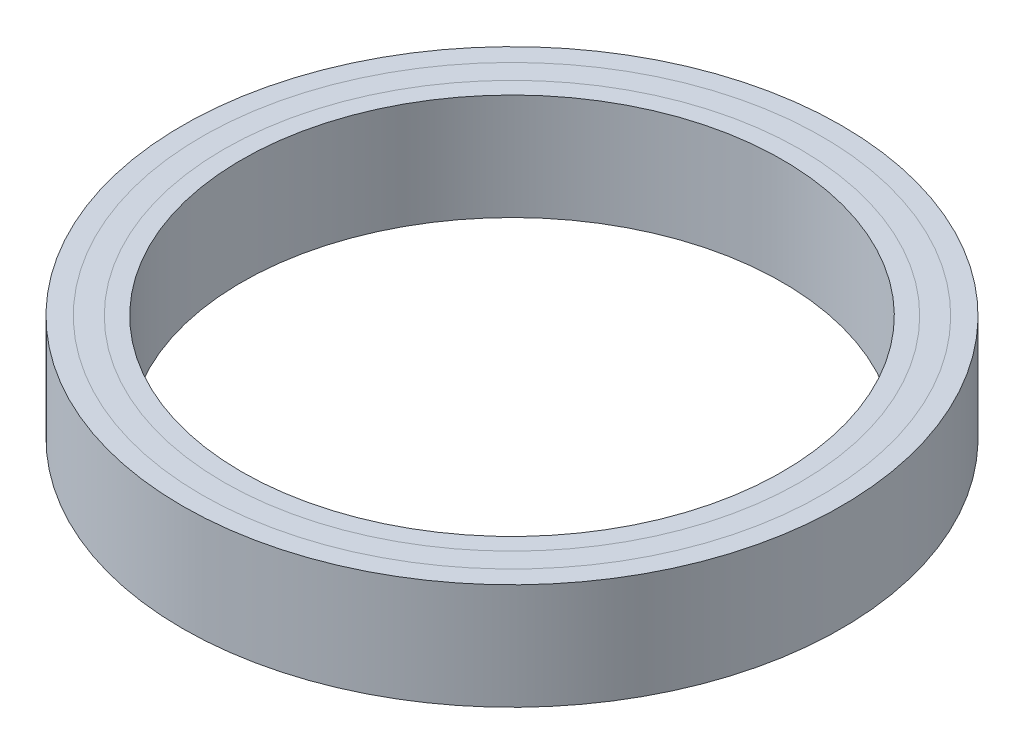
SolidWorks part; units mm, degrees
ref_plane "Front Plane" through (0, 0, 0) normal (0, 0, 1) x (1, 0, 0)
ref_plane "Top Plane" through (0, 0, 0) normal (0, 1, 0) x (1, 0, 0)
ref_plane "Right Plane" through (0, 0, 0) normal (1, 0, 0) x (0, 0, -1)
sketch "Sketch2" plane through (0, 0, 0) normal (0, 1, 0) x (1, 0, 0)
  circle A0 centre (0, 0) radius 21.7376
  circle A1 centre (0, 0) radius 20.3835
extrude "Boss-Extrude1" add sketch "Sketch2" along normal blind 8 from offset 3
sketch "Sketch5" plane through (0, 0, 0) normal (0, 1, 0) x (1, 0, 0)
  circle A0 centre (0, 0) radius 23.3898
  circle A1 centre (0, 0) radius 24.8481
extrude "Boss-Extrude2" add sketch "Sketch5" along normal blind 8 from offset 3 separate body
sketch "Sketch3" plane through (0, 0, 0) normal (0, 0, 1) x (1, 0, 0)
  line L0 (0, 10.5) -> (0, 2.5) construction
  line L3 (20.3835, 11) -> (-20.3835, 11) construction
  line L4 (-38.75, 9.5) -> (-46.25, 9.5)
  line L5 (-38.75, 9.5) -> (-38.75, 4.5)
  line L6 (-38.75, 4.5) -> (-46.25, 4.5)
  line L8 (-46.25, 4.5) -> (-46.25, 9.5)
  line L11 (0, 9) -> (0, 4)
  line L12 (0, 9) -> (0, 4)
  point P6 (0, 6.5)
  dimension "D1" = 5
  dimension "D2" = 38.75
  dimension "D3" = 46.25
  dimension "D4" = 1.5
sketch "Sketch6" plane through (0, 11, 0) normal (0, 1, 0) x (1, 0, 0)
  circle A0 centre (0, 0) radius 21.7376
  circle A1 centre (0, 0) radius 23.3898
extrude "Boss-Extrude3" add sketch "Sketch6" against normal blind 8 separate body
